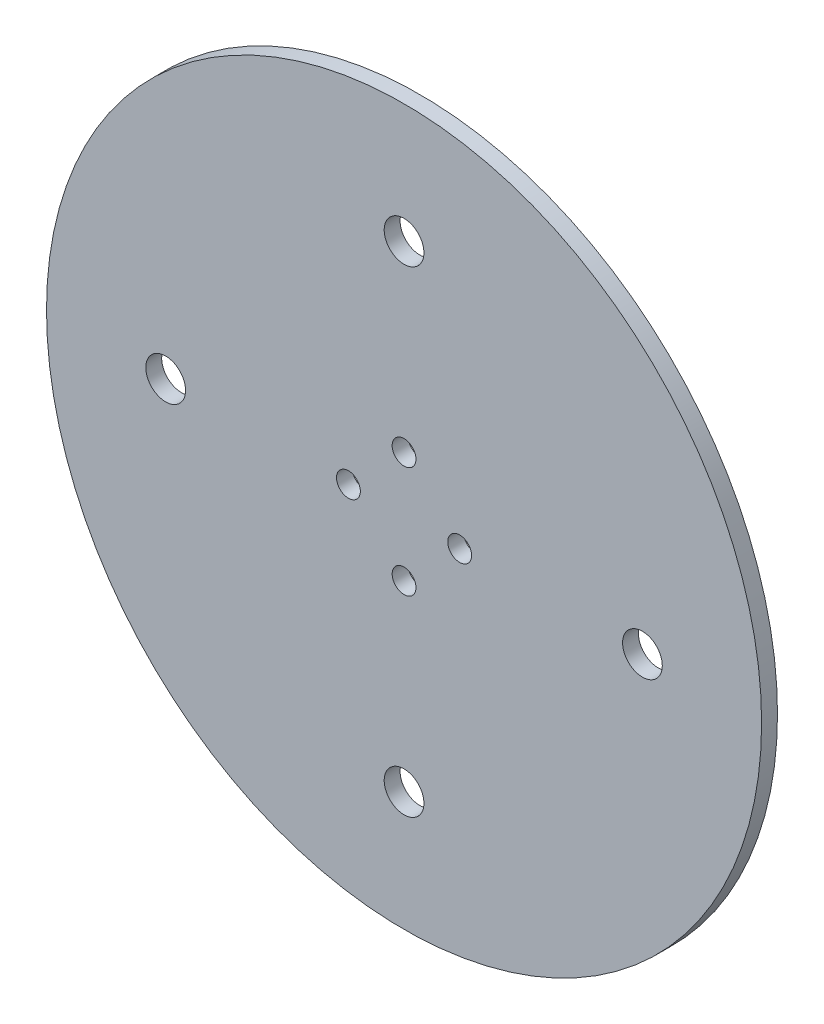
SolidWorks part; units mm, degrees
ref_plane "Front Plane" through (0, 0, 0) normal (0, 0, 1) x (1, 0, 0)
ref_plane "Top Plane" through (0, 0, 0) normal (0, 1, 0) x (1, 0, 0)
ref_plane "Right Plane" through (0, 0, 0) normal (1, 0, 0) x (0, 0, -1)
sketch "Sketch1" plane through (0, 0, 0) normal (0, 0, 1) x (1, 0, 0)
  circle A0 centre (0, 0) radius 45
  circle A1 centre (0, 7) radius 1.5
  circle A2 centre (7, 0) radius 1.5
  circle A3 centre (0, -7) radius 1.5
  circle A4 centre (-7, 0) radius 1.5
  circle A5 centre (0, 30) radius 2.5
  circle A6 centre (30, 0) radius 2.5
  circle A7 centre (0, -30) radius 2.5
  circle A8 centre (-30, 0) radius 2.5
  point P14 (0, 0)
  point P23 (0, 0)
  dimension "D1" = 7
  dimension "D2" = 90
  dimension "D3" = 3
  dimension "D4" = 4
  dimension "D5" = 30
  dimension "D6" = 4
extrude "Boss-Extrude1" add sketch "Sketch1" along normal blind 2
